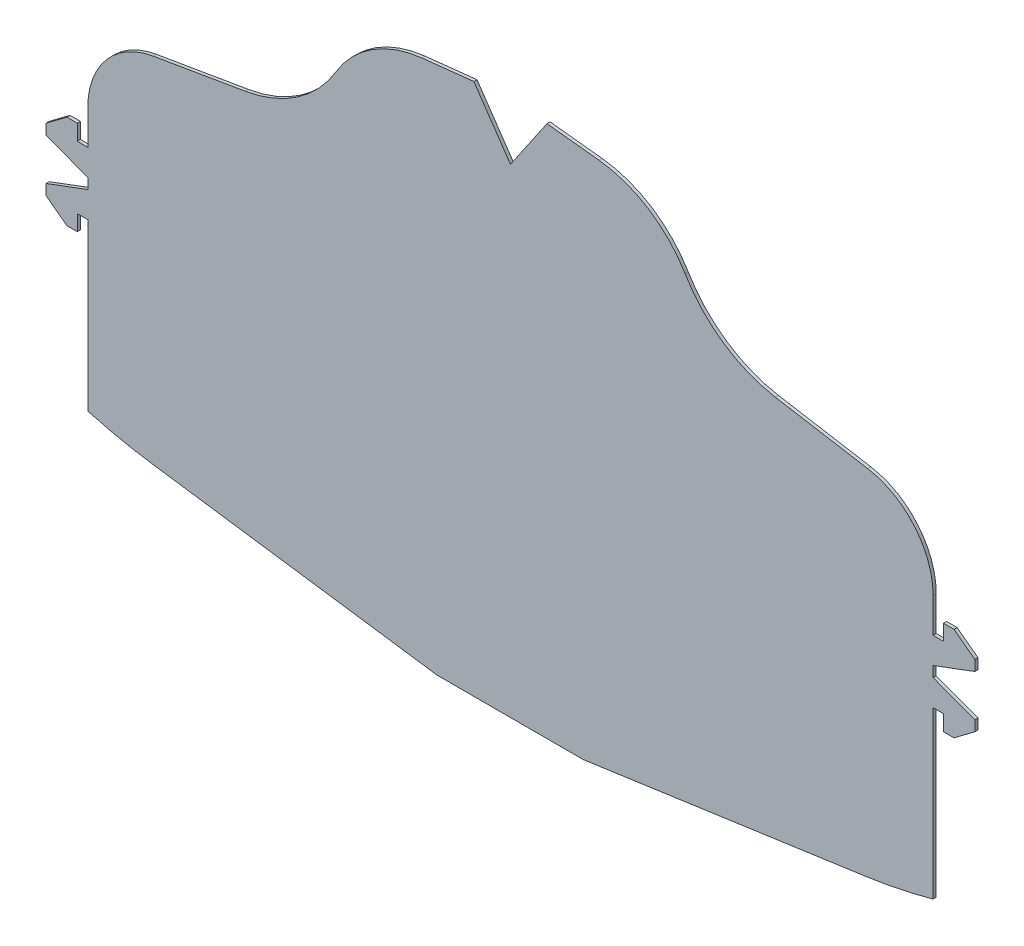
SolidWorks part; units mm, degrees
ref_plane "Front Plane" through (0, 0, 0) normal (0, 0, 1) x (1, 0, 0)
ref_plane "Top Plane" through (0, 0, 0) normal (0, 1, 0) x (1, 0, 0)
ref_plane "Right Plane" through (0, 0, 0) normal (1, 0, 0) x (0, 0, -1)
sketch "Sketch2" plane through (0, 0, 0) normal (0, 0, 1) x (1, 0, 0)
  line L0 (0, -91.7648) -> (0, 10.2352) construction
  line L1 (-14, -91.7648) -> (14, -91.7648)
  line L3 (0, 0) -> (-7, 10.2352)
  line L4 (0, 0) -> (7, 10.2352)
  line L6 (-80.95, -18.3896) -> (-50.7439, -13.2648)
  line L8 (-14, -91.7648) -> (-68.2662, -84.0567)
  line L9 (-7, 10.2352) -> (-16.9419, 9.1584)
  line L12 (14, -91.7648) -> (68.2662, -84.0567)
  line L13 (80.95, -18.3896) -> (50.7439, -13.2648)
  line L14 (7, 10.2352) -> (16.9419, 9.1584)
  line L15 (-80.95, -37.66) -> (-82.95, -37.66)
  line L16 (-82.95, -37.66) -> (-82.95, -34.66)
  line L17 (-82.95, -34.66) -> (-84.95, -34.66)
  line L18 (-84.95, -34.66) -> (-88.95, -37.66)
  line L19 (-88.95, -37.66) -> (-88.95, -39.66)
  line L20 (-88.95, -39.66) -> (-80.95, -42.66)
  line L22 (-80.95, -42.66) -> (-80.95, -44.66)
  line L25 (-88.95, -47.66) -> (-80.95, -44.66)
  line L26 (-88.95, -49.66) -> (-88.95, -47.66)
  line L27 (-84.95, -52.66) -> (-88.95, -49.66)
  line L28 (-82.95, -52.66) -> (-84.95, -52.66)
  line L29 (-82.95, -49.66) -> (-82.95, -52.66)
  line L30 (-80.95, -49.66) -> (-82.95, -49.66)
  line L31 (-80.95, -37.66) -> (-80.95, -18.3896)
  line L33 (-80.95, -49.66) -> (-80.95, -81.4072)
  line L35 (-80.95, -49.66) -> (-80.95, -44.66) construction
  line L37 (-80.95, -42.66) -> (-80.95, -37.66) construction
  line L38 (80.95, -37.66) -> (80.95, -18.3896)
  line L39 (80.95, -49.66) -> (80.95, -81.4072)
  line L40 (80.95, -42.66) -> (80.95, -44.66)
  line L41 (80.95, -37.66) -> (82.95, -37.66)
  line L42 (82.95, -37.66) -> (82.95, -34.66)
  line L43 (82.95, -34.66) -> (84.95, -34.66)
  line L44 (84.95, -34.66) -> (88.95, -37.66)
  line L45 (88.95, -37.66) -> (88.95, -39.66)
  line L46 (88.95, -39.66) -> (80.95, -42.66)
  line L47 (88.95, -47.66) -> (80.95, -44.66)
  line L48 (88.95, -49.66) -> (88.95, -47.66)
  line L49 (84.95, -52.66) -> (88.95, -49.66)
  line L50 (82.95, -52.66) -> (84.95, -52.66)
  line L51 (82.95, -49.66) -> (82.95, -52.66)
  line L52 (80.95, -49.66) -> (82.95, -49.66)
  arc A0 (-16.9419, 9.1584) -> (-33.4614, -1.4344) centre (-14.5729, -12.7137) ccw
  arc A1 (-33.4614, -1.4344) -> (-50.7439, -13.2648) centre (-54.9257, 11.383) cw
  arc A9 (-80.95, -81.4072) -> (-68.2662, -84.0567) centre (-54.2032, 14.9495) ccw
  arc A12 (80.95, -81.4072) -> (68.2662, -84.0567) centre (54.2032, 14.9495) cw
  arc A16 (33.4614, -1.4344) -> (50.7439, -13.2648) centre (54.9257, 11.383) ccw
  arc A17 (16.9419, 9.1584) -> (33.4614, -1.4344) centre (14.5729, -12.7137) cw
  point P3 (0, 0)
  point P9 (0, 0)
  point P43 (-80.95, -42.5638)
  point P45 (-83.95, -34.66)
  point P46 (-88.95, -38.66)
  point P49 (-85.7667, -32.5566)
  point P52 (-87.3006, -34.0175)
  point P56 (-86.7163, -45.3395)
  point P57 (-84.95, -51.7675)
  point P58 (0, 0)
  point P59 (-88.9807, -51.9136)
  point P60 (-84.95, -56.8807)
  point P61 (-88.95, -53.1554)
  point P62 (-84.95, -55.5659)
  point P63 (-84.95, -55.4198)
  point P64 (-80.95, -43.66)
  point P65 (-83.95, -52.66)
  point P86 (0, 0)
  dimension "D8" = 30.6377
  dimension "D11" = 68.2662
  dimension "D13" = 25
  dimension "D15" = 22
  dimension "D18" = 100
  dimension "D22" = 2
  dimension "D1" = 28
  dimension "D2" = 14
  dimension "D3" = 12.4
  dimension "D4" = 10
  dimension "D5" = 102
  dimension "D6" = 188.084
  dimension "D7" = 5
  dimension "D9" = 50.7439
  dimension "D10" = 63.0176
  dimension "D19" = 2
  dimension "D20" = 3
  dimension "D21" = 2
  dimension "D23" = 2
  dimension "D24" = 8
  dimension "D25" = 80.95
  dimension "D26" = 8
  dimension "D27" = 43.66
extrude "Main Shape" add sketch "Sketch2" along normal blind 0.6
fillet "Fillet1" radius 15 2 edges at (80.95, -18.3896, 0.3) (-80.95, -18.3896, 0.3)
